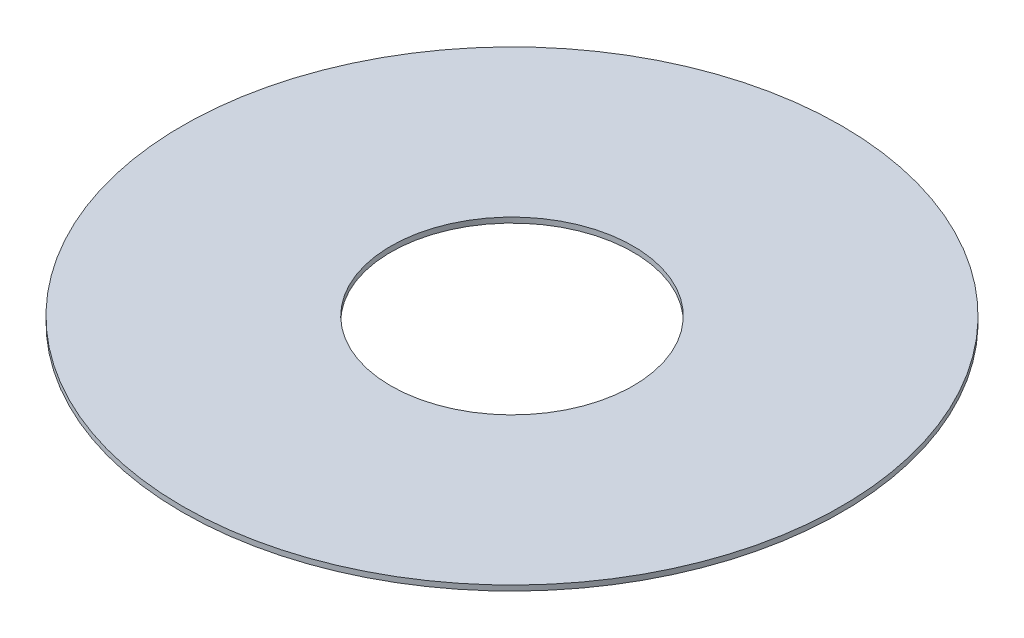
SolidWorks part; units mm, degrees
material "PTFE (general)"
ref_plane "Front Plane" through (0, 0, 0) normal (0, 0, 1) x (1, 0, 0)
ref_plane "Top Plane" through (0, 0, 0) normal (0, 1, 0) x (1, 0, 0)
ref_plane "Right Plane" through (0, 0, 0) normal (1, 0, 0) x (0, 0, -1)
sketch "Sketch1" plane through (0, 0, 0) normal (0, 1, 0) x (0.9995, 0, 0.031)
  circle A2 centre (-29.3916, -2.6114) radius 23.1
  circle A4 centre (-29.3916, -2.6114) radius 62.833
  dimension "D1" = 46.2
extrude "Boss-Extrude1" add sketch "Sketch1" along normal blind 1
